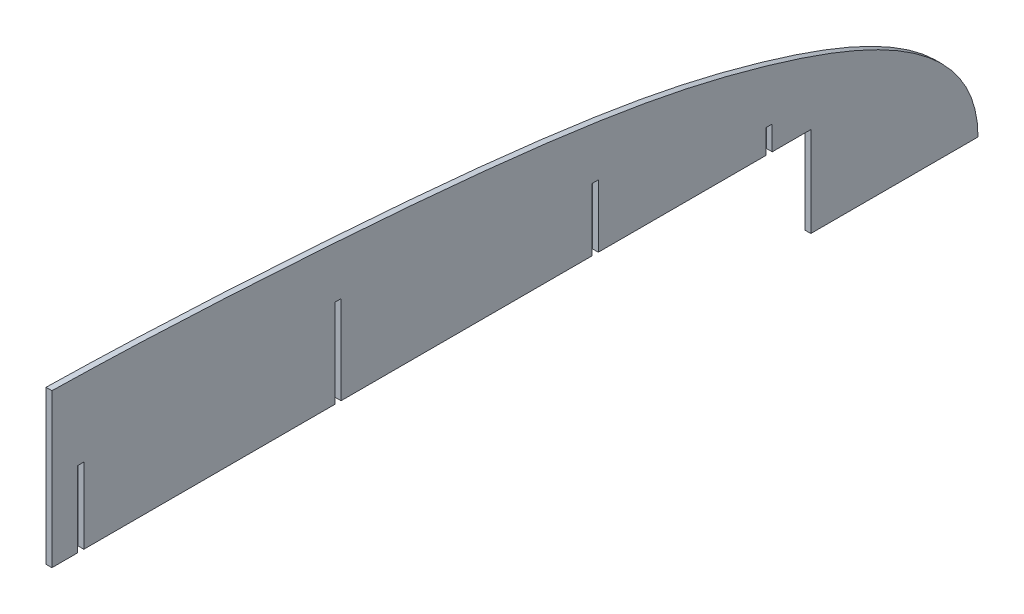
SolidWorks part; units mm, degrees
ref_plane "Front" through (0, 0, 0) normal (0, 0, 1) x (1, 0, 0)
ref_plane "Top" through (0, 0, 0) normal (0, 1, 0) x (1, 0, 0)
ref_plane "Right" through (0, 0, 0) normal (1, 0, 0) x (0, 0, -1)
sketch "Sketch1" plane through (0, 0, 0) normal (1, 0, 0) x (0, 0, -1)
  line L0 (-1460.5, 39.6875) -> (-1460.5, 349.9239) construction
  line L1 (381, 39.6875) -> (381, 279.4) construction
  spline S0 degree 3 poles (-1460.5, 39.6875) (-1460.5, 123.8546) (-1400.449, 238.6436) (-1168.2645, 278.6532) (-889.8632, 278.1926) (-549.517, 284.0694) (-254.873, 268.1625) (-19.654, 247.7534) (192.8383, 207.087) (381, 130.9866) (381, 39.6875) knots 0 0 0 0 0.114448 0.153235 0.341616 0.529763 0.65535 0.781407 0.871202 1 1 1 1
sketch "Sketch2" plane through (0, 0, 0) normal (1, 0, 0) x (0, 0, -1)
  line L0 (-1460.5, 39.6875) -> (381, 39.6875)
  spline S0 degree 3 poles (998.8585, 1535.1716) (-1475.9128, -1119.3171) (-1670.0416, 192.1879) (-1168.2645, 278.6532) (-889.8632, 278.1926) (-549.517, 284.0694) (-254.873, 268.1625) (-19.654, 247.7534) (358.1492, 175.4501) (922.92, -131.3908) (-2227.7873, -1396.0835) knots -0.396656 -0.396656 -0.396656 -0.396656 0.114448 0.153235 0.341616 0.529763 0.65535 0.781407 0.871202 1.268124 1.268124 1.268124 1.268124 only from (-1460.5, 39.6875) to (381, 39.6875) construction
  spline S1 degree 3 poles (-1460.5, 39.6875) (-1460.5, 123.8546) (-1400.449, 238.6436) (-1168.2645, 278.6532) (-889.8632, 278.1926) (-549.517, 284.0694) (-254.873, 268.1625) (-19.654, 247.7534) (192.8383, 207.087) (381, 130.9866) (381, 39.6875) knots 0 0 0 0 0.114448 0.153235 0.341616 0.529763 0.65535 0.781407 0.871202 1 1 1 1
extrude "Boss-Extrude1" add sketch "Sketch2" along normal mid plane 5.842
sketch "Sketch3" plane through (2.921, 0, 0) normal (1, 0, 0) x (0, 0, -1)
  line L0 (215.9, 39.6875) -> (215.9, 128.5875)
  line L1 (-1460.5, 39.6875) -> (381, 39.6875) construction
  line L2 (215.9, 128.5875) -> (177.8, 128.5875)
  line L3 (177.8, 128.5875) -> (177.8, 152.4)
  line L4 (177.8, 152.4) -> (171.704, 152.4)
  line L5 (171.704, 152.4) -> (171.704, 128.5875)
  line L6 (171.704, 128.5875) -> (6.096, 128.5875)
  line L7 (6.096, 128.5875) -> (6.096, 190.5)
  line L8 (6.096, 190.5) -> (0, 190.5)
  line L9 (0, 190.5) -> (0, 128.5875)
  line L10 (0, 128.5875) -> (-247.904, 128.5875)
  line L11 (-533.4, 394.3498) -> (-533.4, 128.5875)
  line L12 (-533.4, 394.3498) -> (-1608.8503, 394.3498)
  line L13 (-1608.8503, 394.3498) -> (-1608.8503, 39.6875)
  line L14 (-1608.8503, 39.6875) -> (215.9, 39.6875)
  line L15 (177.8, 203.2) -> (177.8, 152.4) construction
  line L16 (0, 241.3) -> (0, 190.5) construction
  line L17 (-501.904, 128.5875) -> (-254, 128.5875)
  line L18 (-254, 128.5875) -> (-254, 215.9)
  line L19 (-254, 215.9) -> (-247.904, 215.9)
  line L20 (-247.904, 215.9) -> (-247.904, 128.5875)
  line L21 (-254, 266.7) -> (-254, 215.9) construction
  line L22 (-533.4, 128.5875) -> (-508, 128.5875)
  line L23 (-508, 128.5875) -> (-508, 203.2)
  line L24 (-508, 203.2) -> (-501.904, 203.2)
  line L25 (-501.904, 203.2) -> (-501.904, 128.5875)
  line L26 (-508, 279.4) -> (-508, 203.2) construction
  point P30 (-505.8685, 211.2544)
  dimension "D1" = 38.1
  dimension "D2" = 88.9
  dimension "D3" = 50.8
  dimension "D4" = 6.096
  dimension "D5" = 6.096
  dimension "D6" = 50.8
  dimension "D7" = 50.8
  dimension "D8" = 6.096
  dimension "D9" = 76.2
  dimension "D10" = 6.096
  dimension "D11" = 25.4
extrude "Cut-Extrude1" cut sketch "Sketch3" against normal through all
